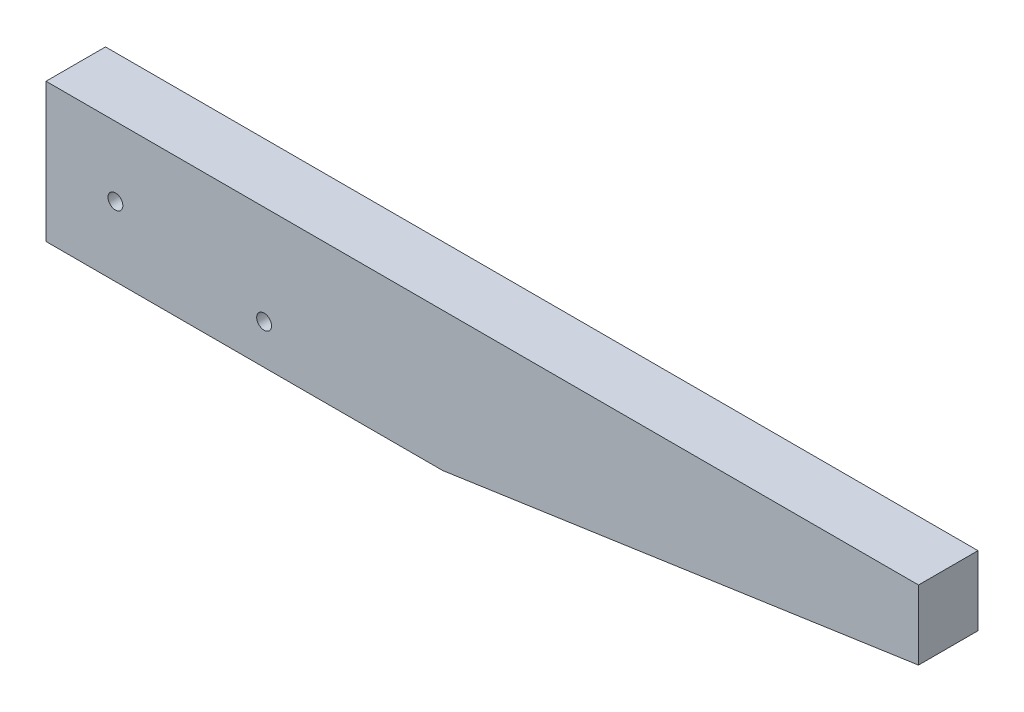
SolidWorks part; units mm, degrees
material "Oak"
ref_plane "Front" through (0, 0, 0) normal (0, 0, 1) x (1, 0, 0)
ref_plane "Top" through (0, 0, 0) normal (0, 1, 0) x (1, 0, 0)
ref_plane "Right" through (0, 0, 0) normal (1, 0, 0) x (0, 0, -1)
sketch "Sketch1" plane through (0, 0, 0) normal (0, 0, 1) x (1, 0, 0)
  line L1 (0, 0) -> (558.8, 0)
  line L2 (0, 0) -> (0, 88.9)
  line L3 (0, 88.9) -> (558.8, 88.9)
  line L4 (558.8, 0) -> (558.8, 88.9)
  dimension "D1" = 558.8
  dimension "D2" = 88.9
extrude "Boss-Extrude1" add sketch "Sketch1" along normal blind 38.1
sketch "Sketch2" plane through (0, 0, 38.1) normal (0, 0, 1) x (1, 0, 0)
  line L0 (0, 0) -> (558.8, 0) construction
  line L1 (0, 0) -> (254, 0)
  line L2 (254, 0) -> (558.8, 44.45)
  line L3 (558.8, 0) -> (558.8, 88.9) construction
  line L4 (558.8, 44.45) -> (558.8, 0)
  line L5 (558.8, 0) -> (254, 0)
  line M2 (0, 0) -> (558.8, 0)
  line M3 (558.8, 0) -> (558.8, 88.9)
  dimension "D1" = 254
extrude "Cut-Extrude1" cut sketch "Sketch2" against normal through all contours L2 M2 M3
hole_wizard "3/8 (0.375) Diameter Hole1" positions "Sketch7" profile "Sketch6" hole size "3/8" standard "ANSI Inch"
sketch "Sketch7" plane through (0, 0, 38.1) normal (0, 0, 1) x (1, 0, 0)
  line L0 (558.8, 88.9) -> (0, 88.9) construction
  line L1 (0, 88.9) -> (0, 0) construction
  point P0 (44.45, 44.45)
  dimension "D1" = 44.45
  dimension "D2" = 44.45
sketch "Sketch6" plane through (44.45, 44.45, 38.1) normal (1, 0, 0) x (0, -1, 0)
  line L0 (0, 0) -> (0, 79.0616)
  line L1 (0, 79.0616) -> (4.7625, 76.2)
  line L2 (4.7625, 76.2) -> (4.7625, 0)
  line L5 (4.7625, 0) -> (0, 0)
  line L10 (0, 79.0616) -> (-4.7625, 76.2) construction
  line L11 (0, -6.35) -> (0, 107.95) construction
  dimension "Hole Dia." = 9.525
  dimension "Hole Depth" = 76.2
  dimension "Drill Angle" = 118
sketch "Sketch8" plane through (0, 0, 38.1) normal (0, 0, 1) x (1, 0, 0)
  line L0 (0, 88.9) -> (0, 0) construction
  line L1 (0, 0) -> (254, 0) construction
  circle A0 centre (139.7, 25.4) radius 4.7625
  dimension "D3" = 9.525
  dimension "D1" = 139.7
  dimension "D2" = 25.4
extrude "Cut-Extrude2" cut sketch "Sketch8" against normal through all
